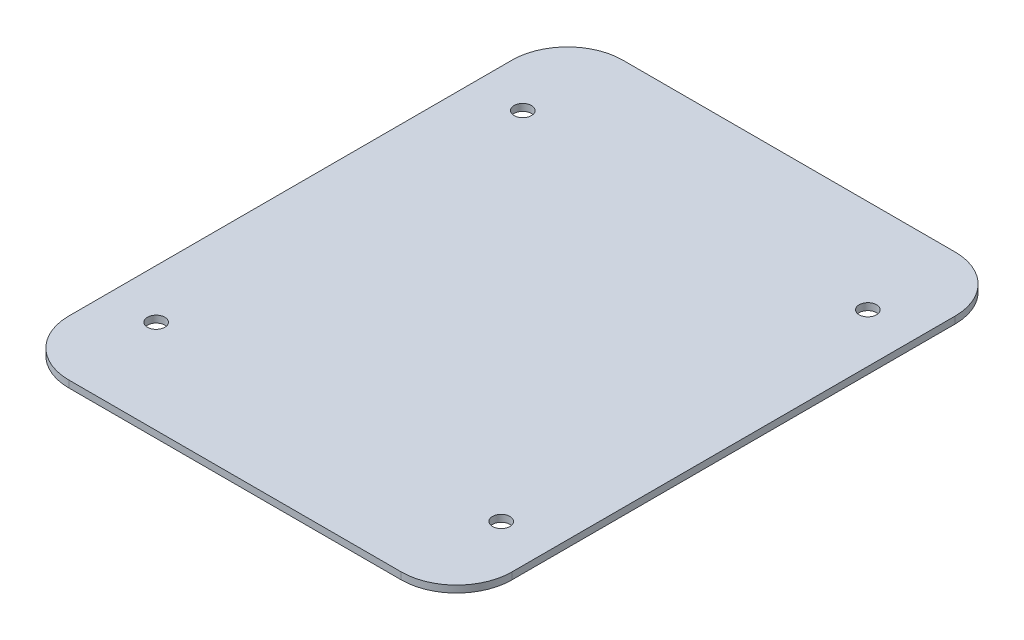
SolidWorks part; units mm, degrees
material "Plain Carbon Steel"
ref_plane "Front" through (0, 0, 0) normal (0, 0, 1) x (1, 0, 0)
ref_plane "Top" through (0, 0, 0) normal (0, 1, 0) x (1, 0, 0)
ref_plane "Right" through (0, 0, 0) normal (1, 0, 0) x (0, 0, -1)
sketch "Sketch1" plane through (0, 0, 0) normal (0, 1, 0) x (1, 0, 0)
  line L1 (-101.6, -127) -> (101.6, -127)
  line L2 (-101.6, -127) -> (-101.6, 127)
  line L3 (-101.6, 127) -> (101.6, 127)
  line L4 (101.6, -127) -> (101.6, 127)
  line L5 (-101.6, -127) -> (101.6, 127) construction
  line L6 (-101.6, 127) -> (101.6, -127) construction
  point P0 (0, 0)
  dimension "D1" = 254
  dimension "D2" = 203.2
extrude "Boss-Extrude1" add sketch "Sketch1" along normal blind 3.175
fillet "Fillet1" radius 25.4 4 edges at (-101.6, 1.5875, -127) (-101.6, 1.5875, 127) (101.6, 1.5875, -127) (101.6, 1.5875, 127)
sketch "Sketch2" plane through (0, 0, 0) normal (0, -1, 0) x (1, 0, 0)
  circle A0 centre (-79.1, 84.05) radius 4
  circle A1 centre (79.1, 84.05) radius 4
  circle A2 centre (79.1, -84.05) radius 4
  circle A3 centre (-79.1, -84.05) radius 4
  point P12 (0, 0)
  point P13 (0, 0)
  point P14 (0, 0)
  point P15 (0, 0)
  point P16 (0, 0)
  point P17 (0, 0)
  point P18 (0, 0)
  point P19 (0, 0)
  dimension "D1" = 8
  dimension "D2" = 158.2
  dimension "D3" = 79.1
  dimension "D4" = 168.1
  dimension "D5" = 84.05
extrude "Cut-Extrude1" cut sketch "Sketch2" against normal blind 25.4
